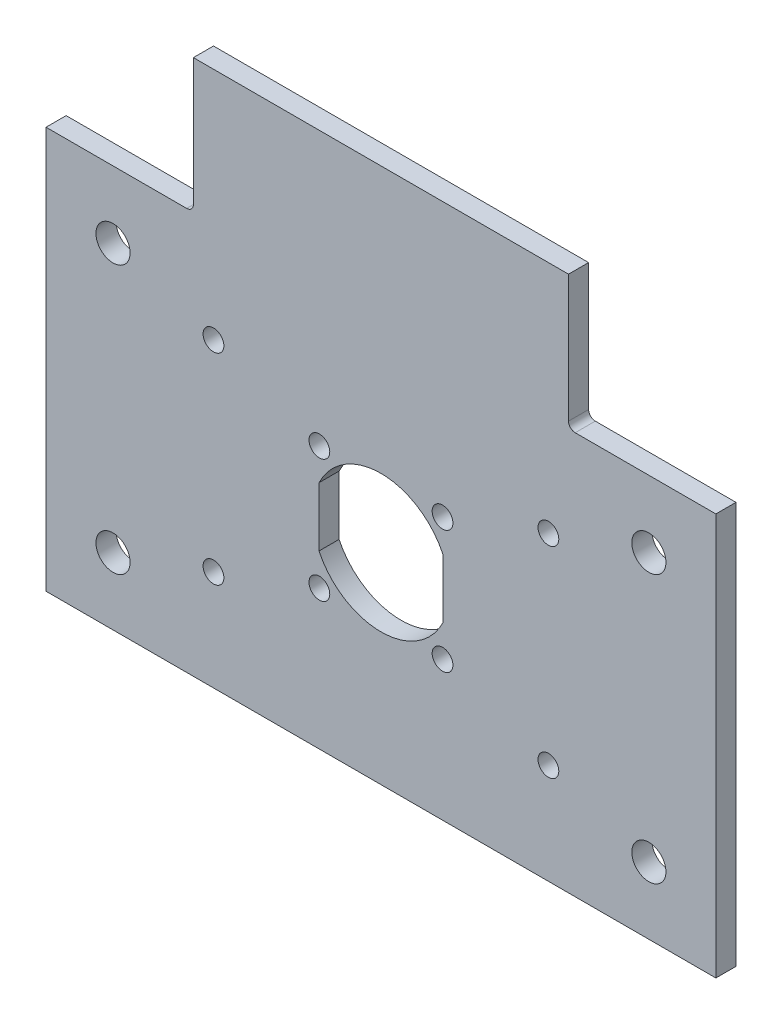
SolidWorks part; units mm, degrees
ref_plane "正面" through (0, 0, 0) normal (0, 0, 1) x (1, 0, 0)
ref_plane "平面" through (0, 0, 0) normal (0, 1, 0) x (1, 0, 0)
ref_plane "右側面" through (0, 0, 0) normal (1, 0, 0) x (0, 0, -1)
sketch "ｽｹｯﾁ1" plane through (0, 0, 0) normal (0, 0, 1) x (1, 0, 0)
  line L0 (-28, 80) -> (-28, 60)
  line L1 (-28, 60) -> (-50, 60)
  line L2 (-50, 60) -> (-50, 0)
  line L3 (-50, 0) -> (50, 0)
  line L4 (0, 0) -> (0, 80) construction
  line L5 (28, 80) -> (-28, 80)
  line L6 (28, 80) -> (28, 60)
  line L7 (28, 60) -> (50, 60)
  line L8 (50, 60) -> (50, 0)
  line L9 (-9.25, 34.4159) -> (-9.25, 25.5841)
  line L10 (-9.25, 30) -> (9.25, 30) construction
  line L11 (9.25, 34.4159) -> (9.25, 25.5841)
  arc A0 (-9.25, 25.5841) -> (9.25, 25.5841) centre (0, 30) ccw
  arc A1 (9.25, 34.4159) -> (-9.25, 34.4159) centre (0, 30) ccw
  point P19 (0, 30)
  dimension "D5" = 18.5
  dimension "D6" = 20.5
  dimension "D1" = 20
  dimension "D2" = 22
  dimension "D3" = 50
  dimension "D4" = 60
  dimension "D7" = 30
extrude "ﾎﾞｽ - 押し出し1" add sketch "ｽｹｯﾁ1" along normal blind 3
sketch "ｽｹｯﾁ2" plane through (0, 0, 3) normal (0, 0, 1) x (1, 0, 0)
  line L0 (9.25, 25.5841) -> (-9.25, 34.4159) construction
  line L1 (-9.25, 25.5841) -> (9.25, 34.4159) construction
  line L2 (-9.1924, 39.1924) -> (9.1924, 20.8076) construction
  line L3 (0, 0) -> (0, 80) construction
  line L4 (28, 80) -> (-28, 80) construction
  circle A0 centre (-9.1924, 39.1924) radius 1.55
  circle A1 centre (9.1924, 39.1924) radius 1.55
  circle A2 centre (9.1924, 20.8076) radius 1.55
  circle A3 centre (-9.1924, 20.8076) radius 1.55
  point P8 (0, 30)
  point P14 (0, 30)
  dimension "D1" = 3.1
  dimension "D2" = 26
  dimension "D4" = 45
  dimension "D3" = 4
extrude "ｶｯﾄ - 押し出し1" cut sketch "ｽｹｯﾁ2" against normal through all
fillet "ﾌｨﾚｯﾄ1" radius 1 2 edges at (28, 60, 1.5) (-28, 60, 1.5)
sketch "ｽｹｯﾁ3" plane through (0, 0, 3) normal (0, 0, 1) x (1, 0, 0)
  line L0 (-40, 60) -> (-40, 0) construction
  line L1 (-29, 60) -> (-50, 60) construction
  line L2 (-50, 0) -> (50, 0) construction
  line L3 (-50, 60) -> (-50, 0) construction
  line L4 (-50, 30) -> (50, 30) construction
  line L5 (50, 0) -> (50, 60) construction
  line L6 (0, 0) -> (0, 80) construction
  line L7 (28, 80) -> (-28, 80) construction
  circle A0 centre (-40, 50) radius 2.55
  circle A1 centre (-40, 10) radius 2.55
  circle A2 centre (40, 10) radius 2.55
  circle A3 centre (40, 50) radius 2.55
  dimension "D2" = 10
  dimension "D3" = 5.1
  dimension "D1" = 10
extrude "ｶｯﾄ - 押し出し2" cut sketch "ｽｹｯﾁ3" against normal through all
sketch "ｽｹｯﾁ4" plane through (0, 0, 3) normal (0, 0, 1) x (1, 0, 0)
  line L0 (-50, 60) -> (50, 0) construction
  line L1 (25, 45) -> (25, 15) construction
  line L2 (50, 60) -> (-50, 0) construction
  line L3 (25, 15) -> (-25, 15) construction
  line L4 (-25, 15) -> (-25, 45) construction
  line L5 (-25, 45) -> (25, 45) construction
  circle A0 centre (25, 45) radius 1.55
  circle A1 centre (25, 15) radius 1.55
  circle A2 centre (-25, 15) radius 1.55
  circle A3 centre (-25, 45) radius 1.55
  point P4 (0, 30)
  dimension "D1" = 3.1
  dimension "D2" = 50
extrude "ｶｯﾄ - 押し出し3" cut sketch "ｽｹｯﾁ4" against normal through all
